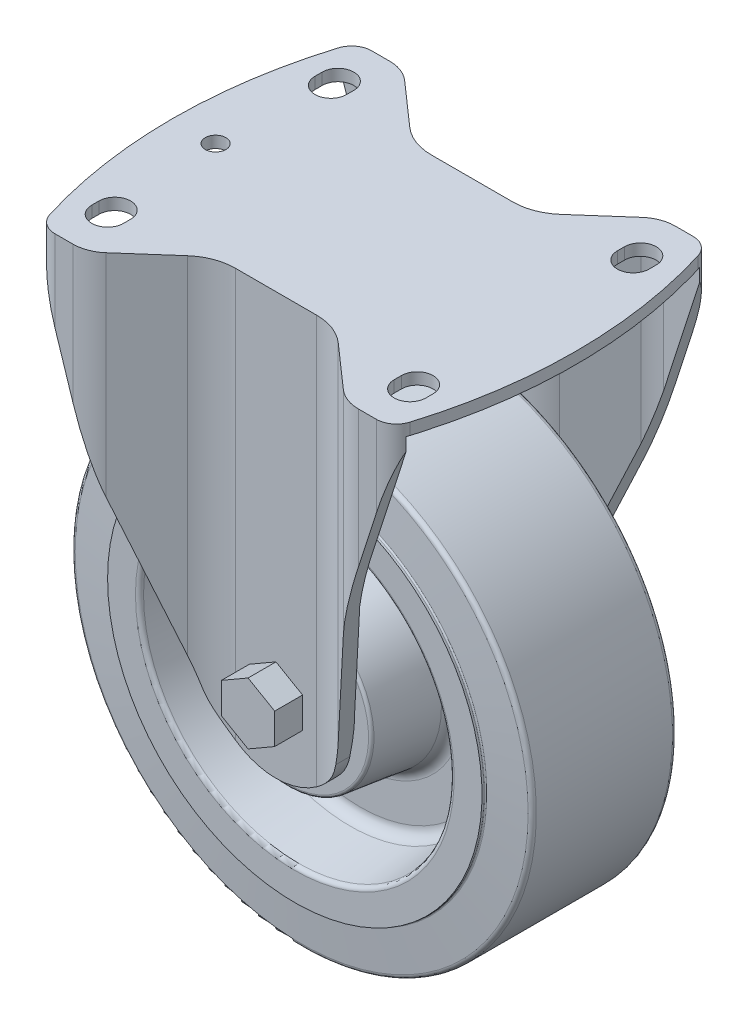
SolidWorks part; units mm, degrees
ref_plane "Front Plane" through (0, 0, 0) normal (0, 0, 1) x (1, 0, 0)
ref_plane "Top Plane" through (0, 0, 0) normal (0, 1, 0) x (1, 0, 0)
ref_plane "Right Plane" through (0, 0, 0) normal (1, 0, 0) x (0, 0, -1)
ref_plane "Plane4" through (0, 122, 0) normal (0, 1, 0) x (1, 0, 0)
sketch "Sketch1" plane through (0, 122, 0) normal (0, 1, 0) x (1, 0, 0)
  line L0 (-55.7878, -55) -> (-49.5565, -55)
  line L1 (-41.2301, -51.8568) -> (-26.1565, -38.5851)
  line L2 (-14.1296, -34.045) -> (14.1296, -34.045)
  line L3 (26.1565, -38.5851) -> (41.2301, -51.8568)
  line L4 (49.5565, -55) -> (55.7878, -55)
  line L5 (55.7878, 55) -> (49.5565, 55)
  line L6 (41.2301, 51.8568) -> (26.1565, 38.5851)
  line L7 (14.1296, 34.045) -> (-14.1296, 34.045)
  line L8 (-26.1565, 38.5851) -> (-41.2301, 51.8568)
  line L9 (-49.5565, 55) -> (-55.7878, 55)
  arc A0 (-62.4787, 50.0571) -> (-62.4787, -50.0571) centre (100.335, 0) ccw
  arc A1 (-62.4787, -50.0571) -> (-55.7878, -55) centre (-55.7878, -48) ccw
  arc A2 (-49.5565, -55) -> (-41.2301, -51.8568) centre (-49.5565, -42.4) ccw
  arc A3 (-26.1565, -38.5851) -> (-14.1296, -34.045) centre (-14.1296, -52.245) cw
  arc A4 (14.1296, -34.045) -> (26.1565, -38.5851) centre (14.1296, -52.245) cw
  arc A5 (41.2301, -51.8568) -> (49.5565, -55) centre (49.5565, -42.4) ccw
  arc A6 (55.7878, -55) -> (62.4787, -50.0571) centre (55.7878, -48) ccw
  arc A7 (62.4787, -50.0571) -> (62.4787, 50.0571) centre (-100.335, 0) ccw
  arc A8 (62.4787, 50.0571) -> (55.7878, 55) centre (55.7878, 48) ccw
  arc A9 (49.5565, 55) -> (41.2301, 51.8568) centre (49.5565, 42.4) ccw
  arc A10 (26.1565, 38.5851) -> (14.1296, 34.045) centre (14.1296, 52.245) cw
  arc A11 (-14.1296, 34.045) -> (-26.1565, 38.5851) centre (-14.1296, 52.245) cw
  arc A12 (-41.2301, 51.8568) -> (-49.5565, 55) centre (-49.5565, 42.4) ccw
  arc A13 (-55.7878, 55) -> (-62.4787, 50.0571) centre (-55.7878, 48) ccw
  circle A22 centre (-55, 0) radius 3.5863
extrude "Boss-Extrude1" add sketch "Sketch1" against normal blind 202
ref_plane "Plane5" through (0, -80.01, 0) normal (0, 1, 0) x (1, 0, 0)
sketch "Sketch2" plane through (0, -80.01, 0) normal (0, 1, 0) x (1, 0, 0)
  line L0 (-93.3333, -50.974) -> (-49.5565, -50.974)
  line L1 (-43.8906, -48.8351) -> (-28.817, -35.5635)
  line L2 (-14.1296, -30.019) -> (14.1296, -30.019)
  line L3 (28.817, -35.5635) -> (43.8906, -48.8351)
  line L4 (49.5565, -50.974) -> (93.3333, -50.974)
  line L5 (93.3333, -50.974) -> (93.3333, 50.974)
  line L6 (93.3333, 50.974) -> (49.5565, 50.974)
  line L7 (43.8906, 48.8351) -> (28.817, 35.5635)
  line L8 (14.1296, 30.019) -> (-14.1296, 30.019)
  line L9 (-28.817, 35.5635) -> (-43.8906, 48.8351)
  line L10 (-49.5565, 50.974) -> (-93.3333, 50.974)
  line L11 (-93.3333, 50.974) -> (-93.3333, -50.974)
  arc A0 (-49.5565, -50.974) -> (-43.8906, -48.8351) centre (-51.043, -38.462) ccw
  arc A1 (-28.817, -35.5635) -> (-14.1296, -30.019) centre (-15.6742, -48.1533) cw
  arc A2 (14.1296, -30.019) -> (28.817, -35.5635) centre (15.6742, -48.1533) cw
  arc A3 (43.8906, -48.8351) -> (49.5565, -50.974) centre (51.043, -38.462) ccw
  arc A4 (49.5565, 50.974) -> (43.8906, 48.8351) centre (51.043, 38.462) ccw
  arc A5 (28.817, 35.5635) -> (14.1296, 30.019) centre (15.6742, 48.1533) cw
  arc A6 (-14.1296, 30.019) -> (-28.817, 35.5635) centre (-15.6742, 48.1533) cw
  arc A7 (-43.8906, 48.8351) -> (-49.5565, 50.974) centre (-51.043, 38.462) ccw
extrude "Cut-Extrude1" cut sketch "Sketch2" along normal blind 197.974
sketch "Sketch3" plane through (0, 0, 0) normal (0, 0, 1) x (1, 0, 0)
  line L0 (-85.5556, -81) -> (85.5556, -81)
  line L1 (85.5556, -81) -> (85.5556, 117.974)
  line L2 (85.5556, 117.974) -> (63.5927, 117.974)
  line L3 (63.5927, 117.974) -> (23.1727, -7.4668)
  line L4 (-23.1727, -7.4668) -> (-63.5927, 117.974)
  line L5 (-63.5927, 117.974) -> (-85.5556, 117.974)
  line L6 (-85.5556, 117.974) -> (-85.5556, -81)
  arc A0 (23.1727, -7.4668) -> (-23.1727, -7.4668) centre (0, 0) cw
extrude "Cut-Extrude2" cut sketch "Sketch3" along normal blind 110 and the other way blind 110
sketch "Sketch4" plane through (0, 122, 0) normal (0, 1, 0) x (1, 0, 0)
  line L0 (58, 37.5) -> (58, 40)
  line L1 (47, 40) -> (47, 37.5)
  arc A0 (47, 37.5) -> (58, 37.5) centre (52.5, 37.5) ccw
  arc A1 (58, 40) -> (47, 40) centre (52.5, 40) ccw
extrude "Cut-Extrude3" cut sketch "Sketch4" against normal blind 65
sketch "Sketch5" plane through (0, 122, 0) normal (0, 1, 0) x (1, 0, 0)
  line L0 (47, -37.5) -> (47, -40)
  line L1 (58, -40) -> (58, -37.5)
  arc A0 (47, -40) -> (58, -40) centre (52.5, -40) ccw
  arc A1 (58, -37.5) -> (47, -37.5) centre (52.5, -37.5) ccw
extrude "Cut-Extrude4" cut sketch "Sketch5" against normal blind 65
sketch "Sketch6" plane through (0, 122, 0) normal (0, 1, 0) x (1, 0, 0)
  line L0 (-47, 37.5) -> (-47, 40)
  line L1 (-58, 40) -> (-58, 37.5)
  arc A0 (-58, 37.5) -> (-47, 37.5) centre (-52.5, 37.5) ccw
  arc A1 (-47, 40) -> (-58, 40) centre (-52.5, 40) ccw
extrude "Cut-Extrude5" cut sketch "Sketch6" against normal blind 65
sketch "Sketch7" plane through (0, 122, 0) normal (0, 1, 0) x (1, 0, 0)
  line L0 (-58, -37.5) -> (-58, -40)
  line L1 (-47, -40) -> (-47, -37.5)
  arc A0 (-58, -40) -> (-47, -40) centre (-52.5, -40) ccw
  arc A1 (-47, -37.5) -> (-58, -37.5) centre (-52.5, -37.5) ccw
extrude "Cut-Extrude6" cut sketch "Sketch7" against normal blind 65
sketch "Sketch8" plane through (0, 0, 0) normal (1, 0, 0) x (0, 0, -1)
  line L0 (-33.55, 0) -> (-33.55, 11.5)
  line L1 (-33.55, 11.5) -> (-31, 11.5)
  line L2 (-31, 11.5) -> (-31, 10)
  line L3 (-31, 10) -> (31, 10)
  line L4 (31, 10) -> (31, 11.5)
  line L5 (31, 11.5) -> (33.55, 11.5)
  line L6 (33.55, 11.5) -> (33.55, 0)
  line L7 (33.55, 0) -> (-33.55, 0)
  line L8 (33.55, 0) -> (-33.55, 0) construction
revolve "Revolve1" add sketch "Sketch8" angle 360 about L8
ref_plane "Plane6" through (0, 0, 43.725) normal (0, 0, 1) x (1, 0, 0)
sketch "Sketch9" plane through (0, 0, 43.725) normal (0, 0, 1) x (1, 0, 0)
  line L0 (-9.24, -5.3347) -> (0, -10.6694)
  line L1 (0, -10.6694) -> (9.24, -5.3347)
  line L2 (9.24, -5.3347) -> (9.24, 5.3347)
  line L3 (9.24, 5.3347) -> (0, 10.6694)
  line L4 (0, 10.6694) -> (-9.24, 5.3347)
  line L5 (-9.24, 5.3347) -> (-9.24, -5.3347)
ref_plane "Plane7" through (0, 0, -43.725) normal (0, 0, 1) x (1, 0, 0)
sketch "Sketch10" plane through (0, 0, -43.725) normal (0, 0, 1) x (1, 0, 0)
  line L0 (-9.24, -5.3347) -> (0, -10.6694)
  line L1 (0, -10.6694) -> (9.24, -5.3347)
  line L2 (9.24, -5.3347) -> (9.24, 5.3347)
  line L3 (9.24, 5.3347) -> (0, 10.6694)
  line L4 (0, 10.6694) -> (-9.24, 5.3347)
  line L5 (-9.24, 5.3347) -> (-9.24, -5.3347)
extrude "Boss-Extrude2" add sketch "Sketch9" against normal blind 9.68
extrude "Boss-Extrude3" add sketch "Sketch10" along normal blind 9.68
sketch "Sketch11" plane through (0, 0, 0) normal (1, 0, 0) x (0, 0, -1)
  line L0 (-30, 28.1153) -> (-30, 9)
  line L1 (-30, 9) -> (30, 9)
  line L2 (30, 9) -> (30, 28.1153)
  line L3 (29.1219, 29.1078) -> (8.2625, 31.669)
  line L4 (4.75, 35.6392) -> (4.75, 47.6678)
  line L5 (8.2625, 51.6379) -> (26.1828, 53.8383)
  line L6 (27.5, 55.3271) -> (27.5, 65)
  line L7 (27.5, 65) -> (26.7705, 65)
  line L8 (26.2724, 65.4564) -> (25.1198, 78.6307)
  line L9 (23.6255, 80) -> (-23.6255, 80)
  line L10 (-25.1198, 78.6307) -> (-26.2724, 65.4564)
  line L11 (-26.7705, 65) -> (-27.5, 65)
  line L12 (-27.5, 65) -> (-27.5, 55.3271)
  line L13 (-26.1828, 53.8383) -> (-8.2625, 51.6379)
  line L14 (-4.75, 47.6678) -> (-4.75, 35.6392)
  line L15 (-8.2625, 31.669) -> (-29.1219, 29.1078)
  line L16 (30, 0) -> (-30, 0) construction
  arc A0 (30, 28.1153) -> (29.1219, 29.1078) centre (29, 28.1153) ccw
  arc A1 (8.2625, 31.669) -> (4.75, 35.6392) centre (8.75, 35.6392) cw
  arc A2 (4.75, 47.6678) -> (8.2625, 51.6379) centre (8.75, 47.6678) cw
  arc A3 (26.1828, 53.8383) -> (27.5, 55.3271) centre (26, 55.3271) ccw
  arc A4 (26.7705, 65) -> (26.2724, 65.4564) centre (26.7705, 65.5) cw
  arc A5 (25.1198, 78.6307) -> (23.6255, 80) centre (23.6255, 78.5) ccw
  arc A6 (-23.6255, 80) -> (-25.1198, 78.6307) centre (-23.6255, 78.5) ccw
  arc A7 (-26.2724, 65.4564) -> (-26.7705, 65) centre (-26.7705, 65.5) cw
  arc A8 (-27.5, 55.3271) -> (-26.1828, 53.8383) centre (-26, 55.3271) ccw
  arc A9 (-8.2625, 51.6379) -> (-4.75, 47.6678) centre (-8.75, 47.6678) cw
  arc A10 (-4.75, 35.6392) -> (-8.2625, 31.669) centre (-8.75, 35.6392) cw
  arc A11 (-29.1219, 29.1078) -> (-30, 28.1153) centre (-29, 28.1153) ccw
revolve "Revolve2" add sketch "Sketch11" angle 360 about L16
